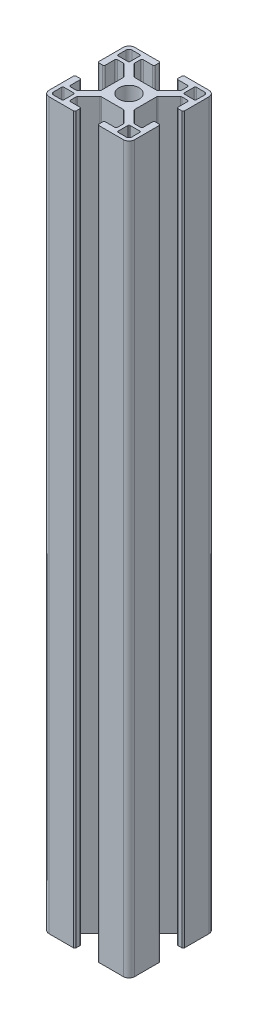
SolidWorks part; units mm, degrees
ref_plane "Front Plane" through (0, 0, 0) normal (0, 0, 1) x (1, 0, 0)
ref_plane "Top Plane" through (0, 0, 0) normal (0, 1, 0) x (1, 0, 0)
ref_plane "Right Plane" through (0, 0, 0) normal (1, 0, 0) x (0, 0, -1)
sketch "Sketch1" plane through (0, 0, 0) normal (0, 1, 0) x (1, 0, 0)
  line L0 (3.9799, -2.4733) -> (3.1981, -1.4942) construction
  line L1 (1.4942, -3.1981) -> (2.4733, -3.9799) construction
  line L2 (-2.4733, -3.9799) -> (-1.4942, -3.1981) construction
  line L3 (-3.1981, -1.4942) -> (-3.9799, -2.4733) construction
  line L4 (-3.9799, 2.4733) -> (-3.1981, 1.4942) construction
  line L5 (-1.4942, 3.1981) -> (-2.4733, 3.9799) construction
  line L6 (2.4733, 3.9799) -> (1.4942, 3.1981) construction
  line L7 (3.1981, 1.4942) -> (3.9799, 2.4733) construction
  line L8 (-12.6999, -13.6999) -> (-9.881, -13.6999)
  line L9 (-13.6999, -9.881) -> (-13.6999, -12.6999)
  line L10 (-9.88, -9.5) -> (-13.3189, -9.5)
  line L11 (-9.5, -13.3189) -> (-9.5, -9.88)
  line L12 (13.6999, -12.6999) -> (13.6999, -9.881)
  line L13 (9.881, -13.6999) -> (12.6999, -13.6999)
  line L14 (9.5, -9.88) -> (9.5, -13.3189)
  line L15 (13.3189, -9.5) -> (9.88, -9.5)
  line L16 (9.88, 9.5) -> (13.3189, 9.5)
  line L17 (9.5, 13.3189) -> (9.5, 9.88)
  line L18 (12.6999, 13.6999) -> (9.881, 13.6999)
  line L19 (13.6999, 9.881) -> (13.6999, 12.6999)
  line L20 (-13.6999, 12.6999) -> (-13.6999, 9.881)
  line L21 (-9.881, 13.6999) -> (-12.6999, 13.6999)
  line L22 (-9.5, 9.88) -> (-9.5, 13.3189)
  line L23 (-13.3189, 9.5) -> (-9.88, 9.5)
  line L24 (14.4999, -4) -> (13.2425, -4)
  line L25 (12.7425, -4.5) -> (12.7425, -7.7325)
  line L26 (12.2428, -8.25) -> (10.2602, -8.25)
  line L27 (9.9066, -8.1035) -> (5.9811, -4.178)
  line L28 (5.8347, -3.8245) -> (5.8347, -1.0125)
  line L29 (5.8347, -1.0125) -> (5.3247, -0.0625) construction
  line L30 (5.3247, -0.0625) -> (5.8347, 0.8875) construction
  line L31 (5.8347, 0.8875) -> (5.8347, 3.8245)
  line L32 (5.9811, 4.178) -> (9.9066, 8.1035)
  line L33 (10.2602, 8.25) -> (12.2428, 8.25)
  line L34 (12.7425, 7.7325) -> (12.7425, 4.5)
  line L35 (13.2425, 4) -> (14.4999, 4)
  line L36 (14.9999, 4.5) -> (14.9999, 12.9999)
  line L37 (12.9999, 14.9999) -> (4.5, 14.9999)
  line L38 (4, 14.4999) -> (4, 13.2425)
  line L39 (4.5, 12.7425) -> (7.7325, 12.7425)
  line L40 (8.25, 12.2428) -> (8.25, 10.2602)
  line L41 (8.1035, 9.9066) -> (4.178, 5.9811)
  line L42 (3.8245, 5.8347) -> (0.95, 5.8347)
  line L43 (0.95, 5.8347) -> (0, 5.3247) construction
  line L44 (0, 5.3247) -> (-0.95, 5.8347) construction
  line L45 (-0.95, 5.8347) -> (-3.8245, 5.8347)
  line L46 (-4.178, 5.9811) -> (-8.1035, 9.9066)
  line L47 (-8.25, 10.2602) -> (-8.25, 12.2428)
  line L48 (-7.7325, 12.7425) -> (-4.5, 12.7425)
  line L49 (-4, 13.2425) -> (-4, 14.4999)
  line L50 (-4.5, 14.9999) -> (-12.9999, 14.9999)
  line L51 (-14.9999, 12.9999) -> (-14.9999, 4.5)
  line L52 (-14.4999, 4) -> (-13.2425, 4)
  line L53 (-12.7425, 4.5) -> (-12.7425, 7.7325)
  line L54 (-12.2428, 8.25) -> (-10.2602, 8.25)
  line L55 (-9.9066, 8.1035) -> (-5.9811, 4.178)
  line L56 (-5.8347, 3.8245) -> (-5.8347, 0.8875)
  line L57 (-5.8347, 0.8875) -> (-5.3247, -0.0625) construction
  line L58 (-5.3247, -0.0625) -> (-5.8347, -1.0125) construction
  line L59 (-5.8347, -1.0125) -> (-5.8347, -3.8245)
  line L60 (-5.9811, -4.178) -> (-9.9066, -8.1035)
  line L61 (-10.2602, -8.25) -> (-12.2428, -8.25)
  line L62 (-12.7425, -7.7325) -> (-12.7425, -4.5)
  line L63 (-13.2425, -4) -> (-14.4999, -4)
  line L64 (-14.9999, -4.5) -> (-14.9999, -12.9999)
  line L65 (-12.9999, -14.9999) -> (-4.5, -14.9999)
  line L66 (-4, -14.4999) -> (-4, -13.2425)
  line L67 (-4.5, -12.7425) -> (-7.7325, -12.7425)
  line L68 (-8.25, -12.2428) -> (-8.25, -10.2602)
  line L69 (-8.1035, -9.9066) -> (-4.178, -5.9811)
  line L70 (-3.8245, -5.8347) -> (-0.95, -5.8347)
  line L71 (-0.95, -5.8347) -> (0, -5.3247) construction
  line L72 (0, -5.3247) -> (0.95, -5.8347) construction
  line L73 (0.95, -5.8347) -> (3.8245, -5.8347)
  line L74 (4.178, -5.9811) -> (8.1035, -9.9066)
  line L75 (8.25, -10.2602) -> (8.25, -12.2428)
  line L76 (7.7325, -12.7425) -> (4.5, -12.7425)
  line L77 (4, -13.2425) -> (4, -14.4999)
  line L78 (4.5, -14.9999) -> (12.9999, -14.9999)
  line L79 (14.9999, -12.9999) -> (14.9999, -4.5)
  line L80 (-5.8347, -1.0125) -> (-5.8347, 0.8875)
  line L81 (-0.95, 5.8347) -> (0.95, 5.8347)
  line L82 (5.8347, 0.8875) -> (5.8347, -1.0125)
  line L83 (-0.95, -5.8347) -> (0.95, -5.8347)
  arc A0 (2.4733, -3.9799) -> (3.9799, -2.4733) centre (3.1422, -3.1422) ccw construction
  arc A1 (-1.4942, -3.1981) -> (1.4942, -3.1981) centre (0, 0) ccw construction
  arc A2 (-3.9799, -2.4733) -> (-2.4733, -3.9799) centre (-3.1422, -3.1422) ccw construction
  arc A3 (-3.1981, 1.4942) -> (-3.1981, -1.4942) centre (0, 0) ccw construction
  arc A4 (-2.4733, 3.9799) -> (-3.9799, 2.4733) centre (-3.1422, 3.1422) ccw construction
  arc A5 (1.4942, 3.1981) -> (-1.4942, 3.1981) centre (0, 0) ccw construction
  arc A6 (3.9799, 2.4733) -> (2.4733, 3.9799) centre (3.1422, 3.1422) ccw construction
  arc A7 (3.1981, -1.4942) -> (3.1981, 1.4942) centre (0, 0) ccw construction
  arc A8 (-13.6999, -12.6999) -> (-12.6999, -13.6999) centre (-12.6999, -12.6999) ccw
  arc A9 (-13.3189, -9.5) -> (-13.6999, -9.881) centre (-13.3189, -9.881) ccw
  arc A10 (-9.5, -9.88) -> (-9.88, -9.5) centre (-9.88, -9.88) ccw
  arc A11 (-9.881, -13.6999) -> (-9.5, -13.3189) centre (-9.881, -13.3189) ccw
  arc A12 (12.6999, -13.6999) -> (13.6999, -12.6999) centre (12.6999, -12.6999) ccw
  arc A13 (9.5, -13.3189) -> (9.881, -13.6999) centre (9.881, -13.3189) ccw
  arc A14 (9.88, -9.5) -> (9.5, -9.88) centre (9.88, -9.88) ccw
  arc A15 (13.6999, -9.881) -> (13.3189, -9.5) centre (13.3189, -9.881) ccw
  arc A16 (9.5, 9.88) -> (9.88, 9.5) centre (9.88, 9.88) ccw
  arc A17 (9.881, 13.6999) -> (9.5, 13.3189) centre (9.881, 13.3189) ccw
  arc A18 (13.6999, 12.6999) -> (12.6999, 13.6999) centre (12.6999, 12.6999) ccw
  arc A19 (13.3189, 9.5) -> (13.6999, 9.881) centre (13.3189, 9.881) ccw
  arc A20 (14.9999, -4.5) -> (14.4999, -4) centre (14.4999, -4.5) ccw
  arc A21 (13.2425, -4) -> (12.7425, -4.5) centre (13.2425, -4.5) ccw
  arc A22 (12.2428, -8.25) -> (12.7425, -7.7325) centre (12.2428, -7.75) ccw
  arc A23 (9.9066, -8.1035) -> (10.2602, -8.25) centre (10.2602, -7.75) ccw
  arc A24 (5.8347, -3.8245) -> (5.9811, -4.178) centre (6.3347, -3.8245) ccw
  arc A25 (5.9811, 4.178) -> (5.8347, 3.8245) centre (6.3347, 3.8245) ccw
  arc A26 (10.2602, 8.25) -> (9.9066, 8.1035) centre (10.2602, 7.75) ccw
  arc A27 (12.7425, 7.7325) -> (12.2428, 8.25) centre (12.2428, 7.75) ccw
  arc A28 (12.7425, 4.5) -> (13.2425, 4) centre (13.2425, 4.5) ccw
  arc A29 (14.4999, 4) -> (14.9999, 4.5) centre (14.4999, 4.5) ccw
  arc A30 (14.9999, 12.9999) -> (12.9999, 14.9999) centre (12.9999, 12.9999) ccw
  arc A31 (4.5, 14.9999) -> (4, 14.4999) centre (4.5, 14.4999) ccw
  arc A32 (4, 13.2425) -> (4.5, 12.7425) centre (4.5, 13.2425) ccw
  arc A33 (8.25, 12.2428) -> (7.7325, 12.7425) centre (7.75, 12.2428) ccw
  arc A34 (8.1035, 9.9066) -> (8.25, 10.2602) centre (7.75, 10.2602) ccw
  arc A35 (3.8245, 5.8347) -> (4.178, 5.9811) centre (3.8245, 6.3347) ccw
  arc A36 (-4.178, 5.9811) -> (-3.8245, 5.8347) centre (-3.8245, 6.3347) ccw
  arc A37 (-8.25, 10.2602) -> (-8.1035, 9.9066) centre (-7.75, 10.2602) ccw
  arc A38 (-7.7325, 12.7425) -> (-8.25, 12.2428) centre (-7.75, 12.2428) ccw
  arc A39 (-4.5, 12.7425) -> (-4, 13.2425) centre (-4.5, 13.2425) ccw
  arc A40 (-4, 14.4999) -> (-4.5, 14.9999) centre (-4.5, 14.4999) ccw
  arc A41 (-12.9999, 14.9999) -> (-14.9999, 12.9999) centre (-12.9999, 12.9999) ccw
  arc A42 (-14.9999, 4.5) -> (-14.4999, 4) centre (-14.4999, 4.5) ccw
  arc A43 (-13.2425, 4) -> (-12.7425, 4.5) centre (-13.2425, 4.5) ccw
  arc A44 (-12.2428, 8.25) -> (-12.7425, 7.7325) centre (-12.2428, 7.75) ccw
  arc A45 (-9.9066, 8.1035) -> (-10.2602, 8.25) centre (-10.2602, 7.75) ccw
  arc A46 (-5.8347, 3.8245) -> (-5.9811, 4.178) centre (-6.3347, 3.8245) ccw
  arc A47 (-5.9811, -4.178) -> (-5.8347, -3.8245) centre (-6.3347, -3.8245) ccw
  arc A48 (-10.2602, -8.25) -> (-9.9066, -8.1035) centre (-10.2602, -7.75) ccw
  arc A49 (-12.7425, -7.7325) -> (-12.2428, -8.25) centre (-12.2428, -7.75) ccw
  arc A50 (-12.7425, -4.5) -> (-13.2425, -4) centre (-13.2425, -4.5) ccw
  arc A51 (-14.4999, -4) -> (-14.9999, -4.5) centre (-14.4999, -4.5) ccw
  arc A52 (-14.9999, -12.9999) -> (-12.9999, -14.9999) centre (-12.9999, -12.9999) ccw
  arc A53 (-4.5, -14.9999) -> (-4, -14.4999) centre (-4.5, -14.4999) ccw
  arc A54 (-4, -13.2425) -> (-4.5, -12.7425) centre (-4.5, -13.2425) ccw
  arc A55 (-8.25, -12.2428) -> (-7.7325, -12.7425) centre (-7.75, -12.2428) ccw
  arc A56 (-8.1035, -9.9066) -> (-8.25, -10.2602) centre (-7.75, -10.2602) ccw
  arc A57 (-3.8245, -5.8347) -> (-4.178, -5.9811) centre (-3.8245, -6.3347) ccw
  arc A58 (4.178, -5.9811) -> (3.8245, -5.8347) centre (3.8245, -6.3347) ccw
  arc A59 (8.25, -10.2602) -> (8.1035, -9.9066) centre (7.75, -10.2602) ccw
  arc A60 (7.7325, -12.7425) -> (8.25, -12.2428) centre (7.75, -12.2428) ccw
  arc A61 (4.5, -12.7425) -> (4, -13.2425) centre (4.5, -13.2425) ccw
  arc A62 (4, -14.4999) -> (4.5, -14.9999) centre (4.5, -14.4999) ccw
  arc A63 (12.9999, -14.9999) -> (14.9999, -12.9999) centre (12.9999, -12.9999) ccw
  arc A64 (-12.6999, 13.6999) -> (-13.6999, 12.6999) centre (-12.6999, 12.6999) ccw
  arc A65 (-9.5, 13.3189) -> (-9.881, 13.6999) centre (-9.881, 13.3189) ccw
  arc A66 (-9.88, 9.5) -> (-9.5, 9.88) centre (-9.88, 9.88) ccw
  arc A67 (-13.6999, 9.881) -> (-13.3189, 9.5) centre (-13.3189, 9.881) ccw
  circle A68 centre (0, 0) radius 3.53
extrude "Boss-Extrude1" add sketch "Sketch1" along normal mid plane 254
